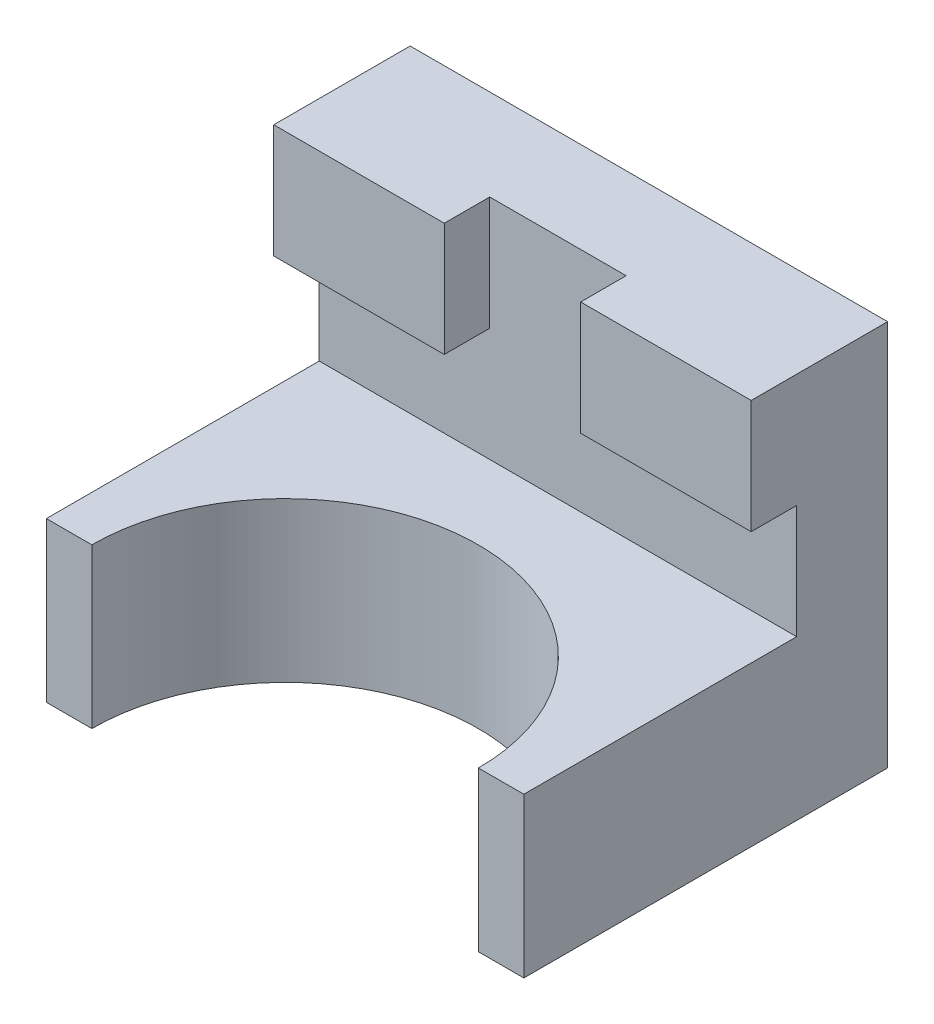
SolidWorks part; units mm, degrees
ref_plane "Спереди" through (0, 0, 0) normal (0, 0, 1) x (1, 0, 0)
ref_plane "Сверху" through (0, 0, 0) normal (0, 1, 0) x (1, 0, 0)
ref_plane "Справа" through (0, 0, 0) normal (1, 0, 0) x (0, 0, -1)
sketch "Эскиз1" plane through (0, 0, 0) normal (0, 1, 0) x (1, 0, 0)
  line L0 (0, 0) -> (105, 0)
  line L1 (105, 0) -> (105, -30)
  line L2 (105, -30) -> (67.5, -30)
  line L3 (67.5, -30) -> (67.5, -20)
  line L4 (67.5, -20) -> (37.5, -20)
  line L5 (37.5, -20) -> (37.5, -30)
  line L6 (37.5, -30) -> (0, -30)
  line L7 (0, -30) -> (0, 0)
  point P3 (36.2344, -20)
  dimension "D1" = 105
  dimension "D2" = 30
  dimension "D3" = 30
  dimension "D4" = 10
  dimension "D5" = 37.5
sketch "Эскиз2" plane through (0, 0, 0) normal (1, 0, 0) x (0, 0, -1)
  line L0 (0, 0) -> (0, -85)
  line L1 (0, -85) -> (-80, -85)
  line L2 (-80, -85) -> (-80, -50)
  line L3 (-80, -50) -> (-20, -50)
  line L4 (-20, -50) -> (-20, -25)
  line L5 (-20, -25) -> (-30, -25)
  line L6 (-30, 0) -> (-30, -25)
  line L7 (0, 0) -> (-30, 0)
  dimension "D1" = 85
  dimension "D2" = 80
  dimension "D3" = 25
  dimension "D4" = 25
  dimension "D5" = 20
extrude "Бобышка-Вытянуть1" add sketch "Эскиз2" along normal blind 105
sketch "Эскиз23" plane through (0, 0, 0) normal (0, 1, 0) x (1, 0, 0)
  line L0 (37.5, -30) -> (37.5, -20)
  line L1 (37.5, -20) -> (67.5, -20)
  line L2 (67.5, -20) -> (67.5, -30)
  line L3 (67.5, -30) -> (37.5, -30)
extrude "Вырез-Вытянуть1" cut sketch "Эскиз23" against normal blind 25
sketch "Эскиз24" plane through (0, -50, 0) normal (0, 1, 0) x (1, 0, 0)
  line L0 (105, -80) -> (0, -80) construction
  circle A0 centre (52.5, -80) radius 42.5
  dimension "D1" = 85
extrude "Вырез-Вытянуть3" cut sketch "Эскиз24" against normal blind 35
